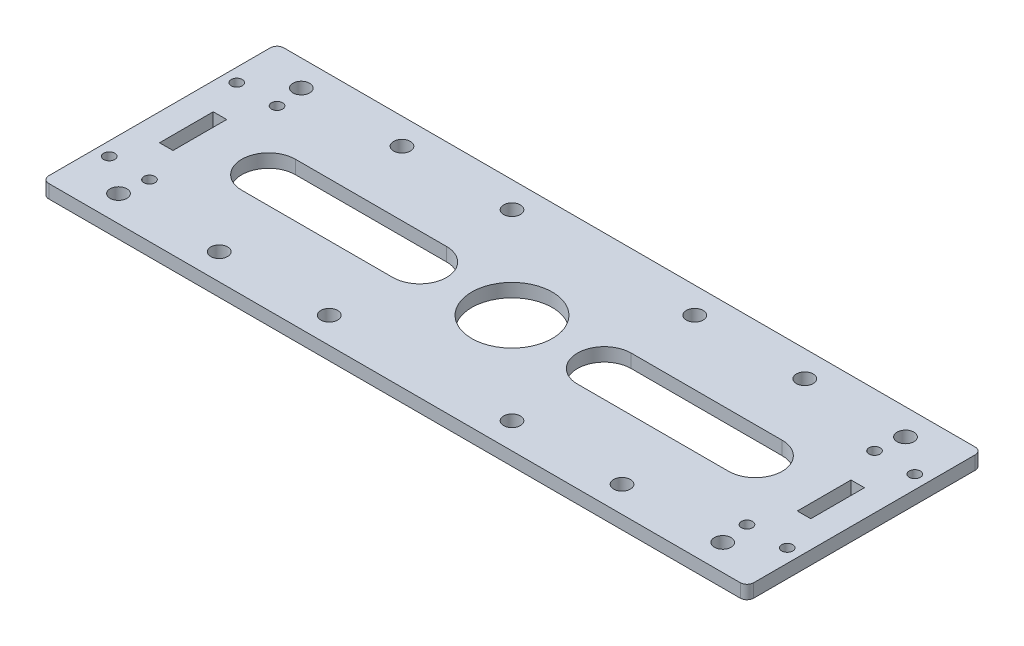
SolidWorks part; units mm, degrees
material "Thornel Mat VMA"
ref_plane "前视基准面" through (0, 0, 0) normal (0, 0, 1) x (1, 0, 0)
ref_plane "上视基准面" through (0, 0, 0) normal (0, 1, 0) x (1, 0, 0)
ref_plane "右视基准面" through (0, 0, 0) normal (1, 0, 0) x (0, 0, -1)
sketch "草图1" plane through (0, 0, 0) normal (0, 1, 0) x (1, 0, 0)
  line L1 (-105, 35) -> (105, 35)
  line L2 (-105, 35) -> (-105, -35)
  line L3 (-105, -35) -> (105, -35)
  line L4 (105, 35) -> (105, -35)
  line L5 (0, -35) -> (0, 35) construction
  line L6 (-105, 0) -> (105, 0) construction
  point P0 (0, 0)
  dimension "D1" = 70
  dimension "D2" = 210
extrude "凸台-拉伸1" add sketch "草图1" along normal blind 4
sketch "草图2" plane through (0, 4, 0) normal (0, 1, 0) x (1, 0, 0)
  line L0 (-105, 0) -> (105, 0) construction
  line L1 (-105, 35) -> (-105, -35) construction
  line L2 (105, -35) -> (105, 35) construction
  line L3 (0, 35) -> (0, -35) construction
  line L4 (105, 35) -> (-105, 35) construction
  line L5 (-105, -35) -> (105, -35) construction
  line L6 (101, 19) -> (66.6991, 19) construction
  circle A0 centre (101, 19) radius 1.65
  circle A1 centre (101, -19) radius 1.65
  circle A2 centre (-101, -19) radius 1.65
  circle A3 centre (-101, 19) radius 1.65
  circle A4 centre (89, 19) radius 1.65
  circle A5 centre (89, -19) radius 1.65
  circle A6 centre (-89, -19) radius 1.65
  circle A7 centre (-89, 19) radius 1.65
  dimension "D1" = 3.3
  dimension "D2" = 4
  dimension "D3" = 38
  dimension "D4" = 3.3
  dimension "D5" = 12
extrude "切除-拉伸1" cut sketch "草图2" against normal blind 50
sketch "草图3" plane through (0, 4, 0) normal (0, 1, 0) x (1, 0, 0)
  line L0 (-105, 0) -> (105, 0) construction
  line L1 (-105, 35) -> (-105, -35) construction
  line L2 (105, -35) -> (105, 35) construction
  line L3 (0, 35) -> (0, -35) construction
  line L4 (105, 35) -> (-105, 35) construction
  line L5 (-105, -35) -> (105, -35) construction
  line L6 (-93, 0) -> (-97, 0) construction
  line L7 (93, 8) -> (97, 8)
  line L8 (93, 8) -> (93, -8)
  line L9 (93, -8) -> (97, -8)
  line L10 (97, 8) -> (97, -8)
  line L11 (95, -8) -> (95, 8) construction
  line L12 (93, 0) -> (97, 0) construction
  line L13 (-95, -8) -> (-95, 8) construction
  line L14 (-97, 8) -> (-97, -8)
  line L15 (-93, -8) -> (-97, -8)
  line L16 (-93, 8) -> (-93, -8)
  line L17 (-93, 8) -> (-97, 8)
  point P12 (95, 0)
  point P24 (-95, 0)
  dimension "D1" = 4
  dimension "D2" = 16
  dimension "D3" = 8
extrude "切除-拉伸2" cut sketch "草图3" against normal blind 50
fillet "圆角1" radius 2 4 edges at (-105, 2, -35) (-105, 2, 35) (105, 2, -35) (105, 2, 35)
sketch "草图7" plane through (0, 4, 0) normal (0, 1, 0) x (1, 0, 0)
  line L0 (0, 35) -> (0, -35) construction
  line L1 (103, 35) -> (-103, 35) construction
  line L2 (-103, -35) -> (103, -35) construction
  line L3 (-105, 0) -> (105, 0) construction
  line L4 (-105, 33) -> (-105, -33) construction
  line L5 (105, -33) -> (105, 33) construction
  line L6 (-27.2236, 27.2236) -> (27.2236, 27.2236) construction
  line L7 (27.2236, 27.2236) -> (27.2236, -27.2236) construction
  line L8 (27.2236, -27.2236) -> (-27.2236, -27.2236) construction
  line L9 (-27.2236, -27.2236) -> (-27.2236, 27.2236) construction
  line L10 (-27.2236, 27.2236) -> (27.2236, -27.2236) construction
  circle A0 centre (27.2236, 27.2236) radius 2.5
  circle A1 centre (-27.2236, 27.2236) radius 2.5
  circle A2 centre (27.2236, -27.2236) radius 2.5
  circle A3 centre (-27.2236, -27.2236) radius 2.5
  dimension "D1" = 5
  dimension "D2" = 45
  dimension "D3" = 77
extrude "切除-拉伸4" cut sketch "草图7" against normal blind 100
sketch "草图8" plane through (0, 4, 0) normal (0, 1, 0) x (1, 0, 0)
  circle A0 centre (0, 0) radius 12
  dimension "D1" = 24
extrude "切除-拉伸5" cut sketch "草图8" against normal blind 10
sketch "草图9" plane through (0, 4, 0) normal (0, 1, 0) x (1, 0, 0)
  line L0 (-105, 0) -> (105, 0) construction
  line L1 (-105, 33) -> (-105, -33) construction
  line L2 (105, -33) -> (105, 33) construction
  line L3 (0, 35) -> (0, -35) construction
  line L4 (103, 35) -> (-103, 35) construction
  line L5 (-103, -35) -> (103, -35) construction
  line L6 (27.5, 0) -> (72.5, 0) construction
  line L7 (27.5, 8) -> (72.5, 8)
  line L8 (27.5, -8) -> (72.5, -8)
  line L9 (-27.5, 0) -> (-72.5, 0) construction
  line L10 (-27.5, 8) -> (-72.5, 8)
  line L11 (-27.5, -8) -> (-72.5, -8)
  arc A0 (27.5, 8) -> (27.5, -8) centre (27.5, 0) ccw
  arc A1 (72.5, -8) -> (72.5, 8) centre (72.5, 0) ccw
  arc A2 (-27.5, 8) -> (-27.5, -8) centre (-27.5, 0) cw
  arc A3 (-72.5, -8) -> (-72.5, 8) centre (-72.5, 0) cw
  point P14 (50, 0)
  point P24 (-50, 0)
  dimension "D1" = 8
  dimension "D2" = 45
  dimension "D3" = 50
extrude "切除-拉伸6" cut sketch "草图9" against normal blind 10
sketch "草图10" plane through (0, 4, 0) normal (0, 1, 0) x (1, 0, 0)
  circle A0 centre (-90, -27.2236) radius 2.5 construction
  circle A1 centre (-60, -27.2236) radius 2.5 construction
  circle A2 centre (60, -27.2236) radius 2.5 construction
  circle A3 centre (90, -27.2236) radius 2.5 construction
  circle A4 centre (90, 27.2236) radius 2.5 construction
  circle A5 centre (60, 27.2236) radius 2.5 construction
  circle A6 centre (-60, 27.2236) radius 2.5 construction
  circle A7 centre (-90, 27.2236) radius 2.5 construction
  circle A8 centre (-90, -27.2236) radius 2.5
  circle A9 centre (-60, -27.2236) radius 2.5
  circle A10 centre (60, -27.2236) radius 2.5
  circle A11 centre (90, -27.2236) radius 2.5
  circle A12 centre (90, 27.2236) radius 2.5
  circle A13 centre (60, 27.2236) radius 2.5
  circle A14 centre (-60, 27.2236) radius 2.5
  circle A15 centre (-90, 27.2236) radius 2.5
extrude "切除-拉伸7" cut sketch "草图10" against normal blind 10
